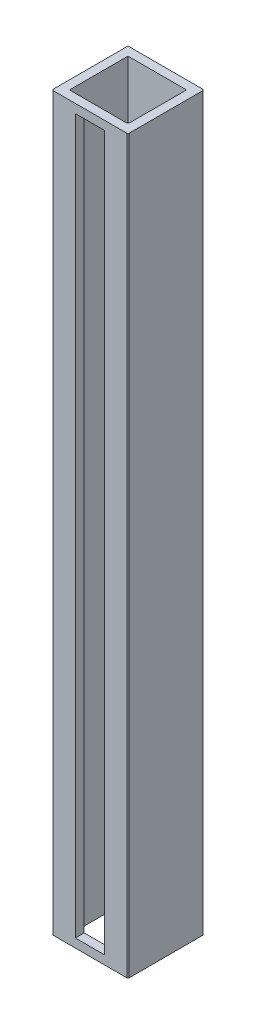
SolidWorks part; units mm, degrees
ref_plane "Front Plane" through (0, 0, 0) normal (0, 0, 1) x (1, 0, 0)
ref_plane "Top Plane" through (0, 0, 0) normal (0, 1, 0) x (1, 0, 0)
ref_plane "Right Plane" through (0, 0, 0) normal (1, 0, 0) x (0, 0, -1)
sketch "Sketch1" plane through (0, 0, 0) normal (0, 1, 0) x (1, 0, 0)
  line L1 (-13, -13) -> (13, -13)
  line L2 (-13, -13) -> (-13, 13)
  line L3 (-13, 13) -> (13, 13)
  line L4 (13, -13) -> (13, 13)
  line L5 (-13, -13) -> (13, 13) construction
  line L6 (-13, 13) -> (13, -13) construction
  point P0 (0, 0)
  dimension "D1" = 26
  dimension "D2" = 26
extrude "Boss-Extrude1" add sketch "Sketch1" along normal blind 250
shell "Shell1" thickness 3
sketch "Sketch2" plane through (0, 0, 13) normal (0, 0, 1) x (1, 0, 0)
  line L0 (-13, 250) -> (-13, 0) construction
  line L1 (5, 3) -> (-5, 3)
  line L2 (5, 3) -> (5, 247)
  line L3 (5, 247) -> (-5, 247)
  line L4 (-5, 3) -> (-5, 247)
  line L5 (5, 3) -> (-5, 247) construction
  line L6 (5, 247) -> (-5, 3) construction
  line L8 (-13, 0) -> (13, 0) construction
  point P0 (0, 125)
  dimension "D1" = 10
  dimension "D2" = 3
  dimension "D3" = 13
  dimension "D4" = 247
extrude "Cut-Extrude1" cut sketch "Sketch2" against normal blind 3
chamfer "Chamfer1" distance 0.3 angle 45 4 edges at (13, 125, -13) (10, 125, 10) (-13, 125, 13) (13, 125, 13)
